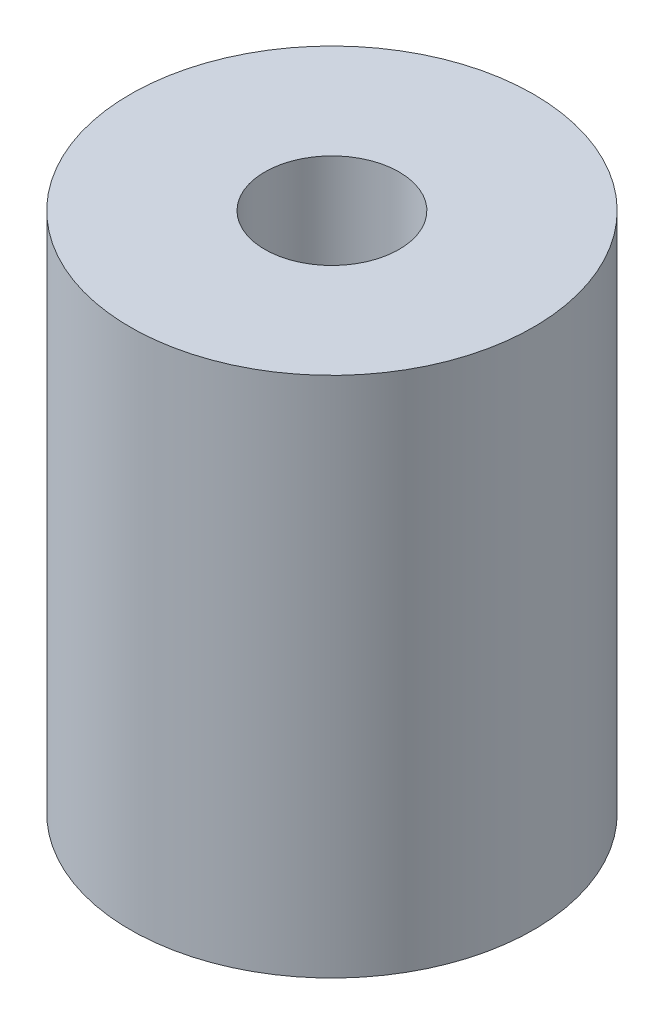
SolidWorks part; units mm, degrees
ref_plane "Front Plane" through (0, 0, 0) normal (0, 0, 1) x (1, 0, 0)
ref_plane "Top Plane" through (0, 0, 0) normal (0, 1, 0) x (1, 0, 0)
ref_plane "Right Plane" through (0, 0, 0) normal (1, 0, 0) x (0, 0, -1)
sketch "Sketch2" plane through (0, 0, 0) normal (0, 1, 0) x (1, 0, 0)
  line L0 (24.0574, -1.8704) -> (0, 0) construction
  line L1 (0, 0) -> (4.1507, -0.3227) construction
  circle A0 centre (10.1397, -0.7884) radius 6.0071
  circle A1 centre (10.1397, -0.7884) radius 2.0003
  dimension "D1" = 12.0142
  dimension "D2" = 4.0005
extrude "Boss-Extrude1" add sketch "Sketch2" along normal mid plane 15.5448
